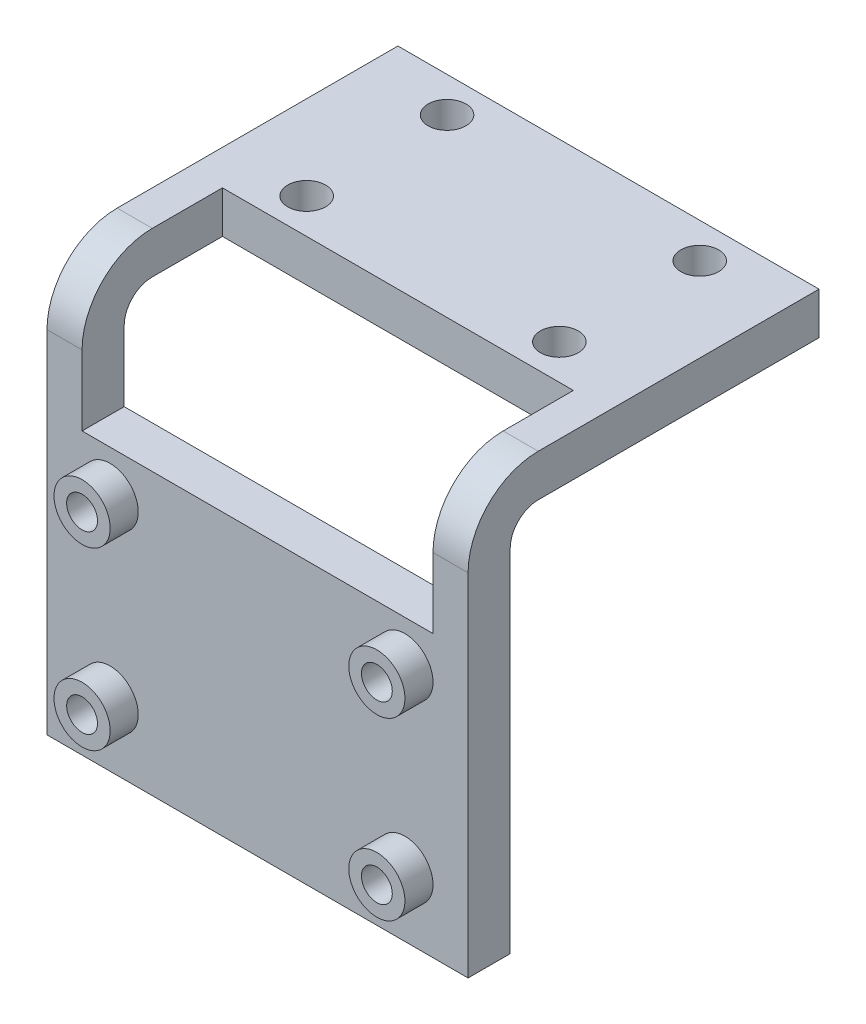
SolidWorks part; units mm, degrees
ref_plane "Front Plane" through (0, 0, 0) normal (0, 0, 1) x (1, 0, 0)
ref_plane "Top Plane" through (0, 0, 0) normal (0, 1, 0) x (1, 0, 0)
ref_plane "Right Plane" through (0, 0, 0) normal (1, 0, 0) x (0, 0, -1)
sketch "Sketch2" plane through (0, 0, 0) normal (0, 0, 1) x (1, 0, 0)
  line L1 (-15, 15) -> (15, 15)
  line L2 (-15, 15) -> (-15, -15)
  line L3 (-15, -15) -> (15, -15)
  line L4 (15, 15) -> (15, -15)
  line L5 (-15, 15) -> (15, -15) construction
  line L6 (-15, -15) -> (15, 15) construction
  point P0 (0, 0)
  dimension "D1" = 30
  dimension "D2" = 30
extrude "Boss-Extrude1" add sketch "Sketch2" along normal blind 3
sketch "Sketch4" plane through (0, 0, 3) normal (0, 0, 1) x (1, 0, 0)
  line L0 (15, -15) -> (15, 15) construction
  line L1 (-15, -15) -> (15, -15) construction
  circle A0 centre (-10.5, 2) radius 2
  circle A1 centre (10.5, 2) radius 2
  circle A2 centre (10.5, -10.5) radius 2
  circle A3 centre (-10.5, -10.5) radius 2
  dimension "D2" = 4
  dimension "D3" = 4
  dimension "D4" = 4.5
  dimension "D5" = 4
  dimension "D6" = 4
  dimension "D8" = 4.5
  dimension "D9" = 12.5
  dimension "D10" = 4.5
  dimension "D1" = 21
  dimension "D7" = 21
extrude "Boss-Extrude2" add sketch "Sketch4" along normal blind 2
sketch "Sketch5" plane through (0, 0, 5) normal (0, 0, 1) x (1, 0, 0)
  circle A0 centre (10.5, 2) radius 1.1
  circle A1 centre (-10.5, 2) radius 1.1
  circle A2 centre (-10.5, -10.5) radius 1.1
  circle A3 centre (10.5, -10.5) radius 1.1
  dimension "D1" = 2.2
  dimension "D2" = 2.2
  dimension "D3" = 2.2
  dimension "D4" = 2.2
extrude "Cut-Extrude1" cut sketch "Sketch5" against normal blind 12
sketch "Sketch6" plane through (0, 0, 3) normal (0, 0, 1) x (1, 0, 0)
  line L1 (-12.5, 12) -> (12.5, 12)
  line L2 (-12.5, 12) -> (-12.5, 5)
  line L3 (-12.5, 5) -> (12.5, 5)
  line L4 (12.5, 12) -> (12.5, 5)
  line L5 (15, -15) -> (15, 15) construction
  line L8 (15, 15) -> (-15, 15) construction
  dimension "D1" = 25
  dimension "D2" = 2.5
  dimension "D3" = 7
  dimension "D4" = 3
extrude "Cut-Extrude2" cut sketch "Sketch6" against normal blind 3
sketch "Sketch9" plane through (0, 0, 0) normal (0, 0, -1) x (-1, 0, 0)
  line L0 (15, 15) -> (15, -15) construction
  line L1 (-15, 15) -> (15, 15)
  line L2 (-15, 15) -> (-15, 12)
  line L3 (-15, 12) -> (15, 12)
  line L4 (15, 15) -> (15, 12)
  dimension "D1" = 3
extrude "Boss-Extrude3" add sketch "Sketch9" along normal blind 22
sketch "Sketch10" plane through (0, 0, 3) normal (0, 0, 1) x (1, 0, 0)
  line L0 (15, 15) -> (-15, 15) construction
  line L1 (-12.5, 12) -> (12.5, 12)
  line L2 (-12.5, 12) -> (-12.5, 15)
  line L3 (-12.5, 15) -> (12.5, 15)
  line L4 (12.5, 12) -> (12.5, 15)
  dimension "D1" = 25
extrude "Cut-Extrude3" cut sketch "Sketch10" against normal blind 10
fillet "Fillet1" radius 2 2 edges at (-13.75, 12, 0) (13.75, 12, 0)
fillet "Fillet2" radius 5 2 edges at (-13.75, 15, 3) (13.75, 15, 3)
sketch "Sketch11" plane through (0, 15, 0) normal (0, 1, 0) x (1, 0, 0)
  line L0 (15, 2) -> (15, 22) construction
  line L1 (12.5, 7) -> (-12.5, 7) construction
  circle A0 centre (-9, 19.5) radius 1.35
  circle A1 centre (9, 19.5) radius 1.35
  circle A2 centre (-9, 9.5) radius 1.35
  circle A3 centre (9, 9.5) radius 1.35
  dimension "D1" = 2.7
  dimension "D2" = 2.7
  dimension "D3" = 2.7
  dimension "D4" = 2.7
  dimension "D5" = 18
  dimension "D6" = 6
  dimension "D7" = 18
  dimension "D8" = 10
  dimension "D9" = 2.5
extrude "Cut-Extrude4" cut sketch "Sketch11" against normal blind 10
